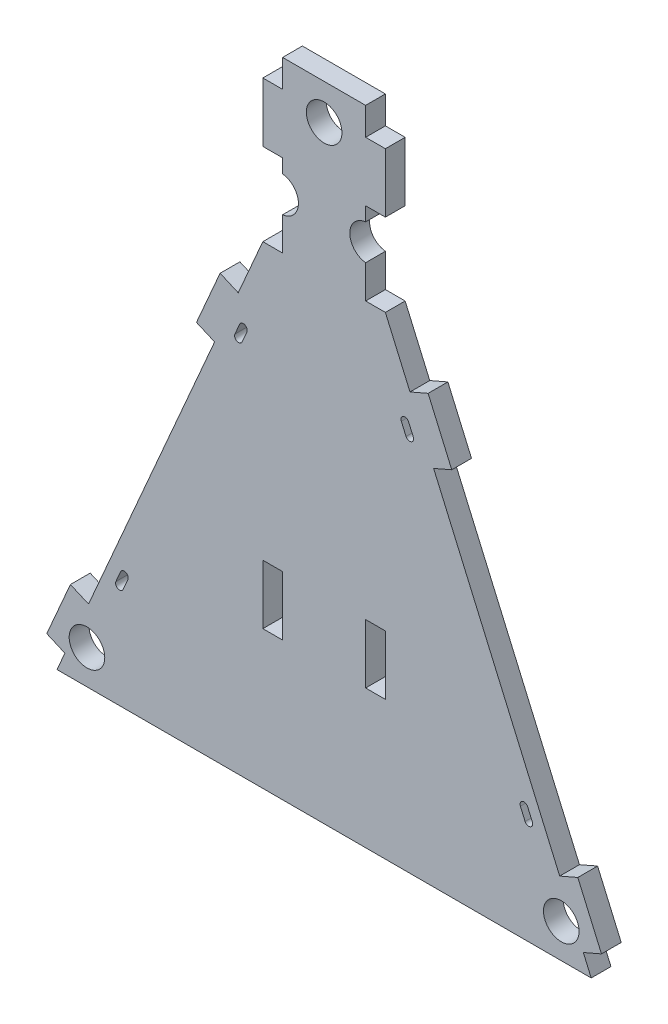
SolidWorks part; units mm, degrees
ref_plane "Front Plane" through (0, 0, 0) normal (0, 0, 1) x (1, 0, 0)
ref_plane "Top Plane" through (0, 0, 0) normal (0, 1, 0) x (1, 0, 0)
ref_plane "Right Plane" through (0, 0, 0) normal (1, 0, 0) x (0, 0, -1)
sketch "Sketch1" plane through (0, 0, 0) normal (0, 0, 1) x (1, 0, 0)
  line L0 (0, 0) -> (67.5684, 0)
  line L3 (0, 162.6488) -> (0, 0)
  line L7 (15.5, 119.7865) -> (67.5684, 0)
  line L8 (10.5, 119.7865) -> (10.5, 128.1754)
  line L9 (10.5, 162.6488) -> (0, 162.6488)
  line L10 (59.5955, 18.3421) -> (27.704, 91.7106) construction
  line L11 (15.5, 119.7865) -> (10.5, 119.7865)
  line L12 (10.5, 158.1936) -> (10.5, 162.9421) construction
  line L18 (10.5, 137.1197) -> (10.5, 162.6488)
  arc A0 (10.5, 137.1197) -> (10.5, 128.1754) centre (11, 132.6475) ccw
  point P8 (-2.3473, 162.6488)
  dimension "D1" = 5
  dimension "D2" = 9
extrude "Boss-Extrude1" add sketch "Sketch1" along normal blind 5
sketch "Sketch3" plane through (0, 0, 5) normal (0, 0, 1) x (1, 0, 0)
  line L0 (65.5752, 4.5855) -> (59.5955, 18.3421)
  line L1 (65.5752, 4.5855) -> (70.1607, 6.5787)
  line L2 (59.5955, 18.3421) -> (64.181, 20.3353)
  line L3 (70.1607, 6.5787) -> (64.181, 20.3353)
  line L4 (67.5684, 0) -> (15.5, 119.7865) construction
  line L5 (27.704, 91.7106) -> (21.7243, 105.4671)
  line L6 (27.704, 91.7106) -> (32.2895, 93.7038)
  line L7 (21.7243, 105.4671) -> (26.3098, 107.4604)
  line L8 (32.2895, 93.7038) -> (26.3098, 107.4604)
  line L9 (10.5, 155.6488) -> (10.5, 140.6488)
  line L10 (10.5, 155.6488) -> (15.5, 155.6488)
  line L11 (10.5, 140.6488) -> (15.5, 140.6488)
  line L12 (15.5, 155.6488) -> (15.5, 140.6488)
  line L13 (10.5, 119.7865) -> (10.5, 128.1754) construction
  line L14 (10.5, 162.6488) -> (0, 162.6488) construction
  dimension "D1" = 5
  dimension "D2" = 15
  dimension "D3" = 5
  dimension "D4" = 80
  dimension "D5" = 7
extrude "Boss-Extrude2" add sketch "Sketch3" against normal up to surface (5 mm away) up to face at (15.1335, 103.7707, 0)
mirror "Mirror1" about plane through (0, 162.6488, 5) normal (1, 0, 0) of "Boss-Extrude2", "Boss-Extrude1"
sketch "Sketch4" plane through (0, 0, 5) normal (0, 0, 1) x (1, 0, 0)
  circle A0 centre (0, 153.6489) radius 4.5
  circle A1 centre (-59.9926, 8.6489) radius 4.5
  circle A2 centre (59.9926, 8.6489) radius 4.5
  dimension "D1" = 9
extrude "Cut-Extrude1" cut sketch "Sketch4" against normal through all
sketch "Sketch5" plane through (0, 0, 5) normal (0, 0, 1) x (1, 0, 0)
  line L0 (15.5, 35) -> (15.5, 50) construction
  line L1 (15.5, 50) -> (10.5, 50) construction
  line L2 (10.5, 50) -> (10.5, 35) construction
  line L3 (10.5, 35) -> (15.5, 35) construction
  line L4 (-10.5, 35) -> (-10.5, 50) construction
  line L5 (-10.5, 50) -> (-15.5, 50) construction
  line L6 (-15.5, 50) -> (-15.5, 35) construction
  line L7 (-15.5, 35) -> (-10.5, 35) construction
  line L8 (15.5, 35) -> (15.5, 50)
  line L9 (15.5, 50) -> (10.5, 50)
  line L10 (10.5, 50) -> (10.5, 35)
  line L11 (10.5, 35) -> (15.5, 35)
  line L12 (-10.5, 35) -> (-10.5, 50)
  line L13 (-10.5, 50) -> (-15.5, 50)
  line L14 (-15.5, 50) -> (-15.5, 35)
  line L15 (-15.5, 35) -> (-10.5, 35)
extrude "Cut-Extrude2" cut sketch "Sketch5" against normal through all
sketch "Sketch6" plane through (0, 0, 5) normal (0, 0, 1) x (1, 0, 0)
  line L0 (-51.7605, 26.3331) -> (-50.5645, 29.0844) construction
  line L1 (-52.6776, 26.7317) -> (-51.4816, 29.483)
  line L2 (-50.8434, 25.9344) -> (-49.6474, 28.6857)
  line L3 (-21.6437, 95.6186) -> (-20.4477, 98.3699) construction
  line L4 (-22.5608, 96.0173) -> (-21.3648, 98.7686)
  line L5 (-20.7266, 95.22) -> (-19.5306, 97.9713)
  line L6 (-60.0144, 29.9209) -> (-58.8185, 32.6722) construction
  line L7 (-59.5955, 18.3421) -> (-27.704, 91.7106) construction
  line L8 (-59.5955, 18.3421) -> (-27.704, 91.7106) construction
  line L9 (-60.0144, 29.9209) -> (-58.8185, 32.6722) construction
  line L10 (-59.4165, 31.2965) -> (-52.0796, 28.1074) construction
  line L11 (-50.5645, 29.0844) -> (-21.6437, 95.6186) construction
  line L12 (-29.2997, 100.5821) -> (-21.9628, 97.3929) construction
  line L13 (-32.2895, 93.7038) -> (-26.3098, 107.4604) construction
  arc A0 (-52.6776, 26.7317) -> (-50.8434, 25.9344) centre (-51.7605, 26.3331) ccw
  arc A1 (-49.6474, 28.6857) -> (-51.4816, 29.483) centre (-50.5645, 29.0844) ccw
  arc A2 (-22.5608, 96.0173) -> (-20.7266, 95.22) centre (-21.6437, 95.6186) ccw
  arc A3 (-19.5306, 97.9713) -> (-21.3648, 98.7686) centre (-20.4477, 98.3699) ccw
  point P2 (-51.1625, 27.7087)
  point P7 (-21.0457, 96.9943)
  dimension "D1" = 2
  dimension "D2" = 3
  dimension "D3" = 3
extrude "Cut-Extrude3" cut sketch "Sketch6" against normal through all
mirror "Mirror2" about plane through (0, 0, 0) normal (1, 0, 0) of "Cut-Extrude3"
equation "\"D1@Sketch3\"=\"thickness_plates@ankare 3 linor.Assembly\""
equation "\"D2@Sketch3\"=\"tab_slot_length@ankare 3 linor.Assembly\""
